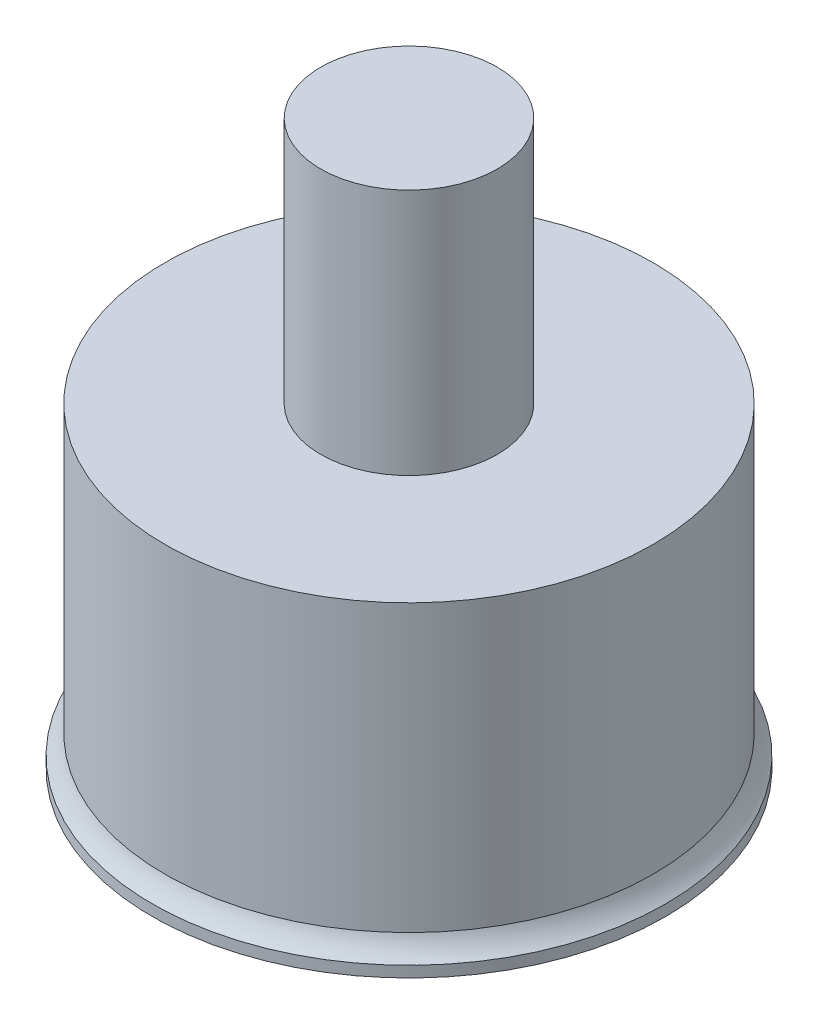
SolidWorks part; units mm, degrees
ref_plane "Front Plane" through (0, 0, 0) normal (0, 0, 1) x (1, 0, 0)
ref_plane "Top Plane" through (0, 0, 0) normal (0, 1, 0) x (1, 0, 0)
ref_plane "Right Plane" through (0, 0, 0) normal (1, 0, 0) x (0, 0, -1)
sketch "Sketch1" plane through (0, 0, 0) normal (0, 0, 1) x (1, 0, 0)
  line L0 (0, 63.8) -> (0, 0) construction
  line L1 (0, 0) -> (29.07, 0) construction
  line L2 (29.07, 0) -> (29.07, 1.25)
  line L3 (27.65, 35.8) -> (27.65, 3.45)
  line L4 (27.65, 35.8) -> (10, 35.8)
  line L5 (10, 35.8) -> (10, 63.8)
  line L6 (0, 63.8) -> (10, 63.8)
  line L7 (29.07, 0) -> (0, 0)
  line L8 (0, 0) -> (0, 63.8)
  arc A0 (27.65, 3.45) -> (29.07, 1.25) centre (32.4143, 4.9669) ccw
  dimension "D8" = 5
  dimension "D1" = 10
  dimension "D2" = 28
  dimension "D3" = 35.8
  dimension "D4" = 1.25
  dimension "D5" = 27.65
  dimension "D6" = 29.07
  dimension "D7" = 3.45
revolve "Revolve1" add sketch "Sketch1" angle 360 about L8
